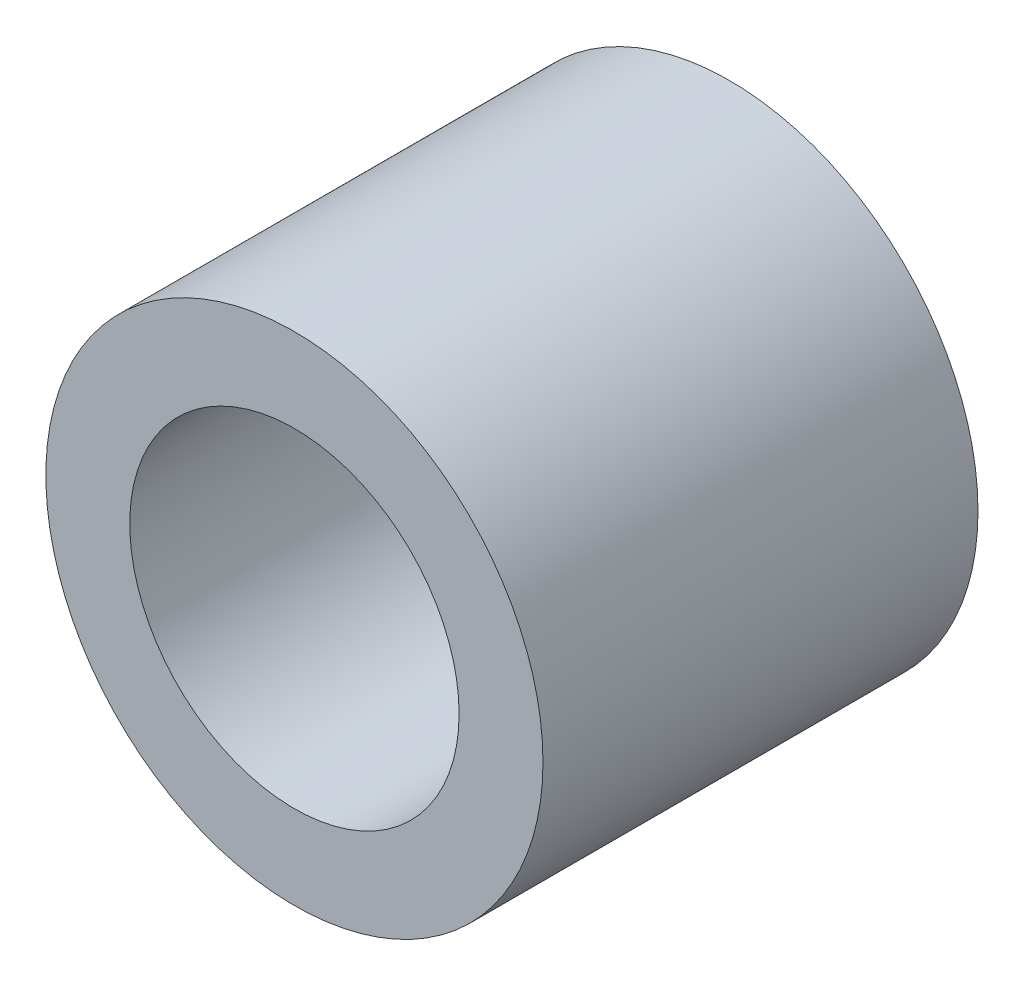
SolidWorks part; units mm, degrees
ref_plane "Front Plane" through (0, 0, 0) normal (0, 0, 1) x (1, 0, 0)
ref_plane "Top Plane" through (0, 0, 0) normal (0, 1, 0) x (1, 0, 0)
ref_plane "Right Plane" through (0, 0, 0) normal (1, 0, 0) x (0, 0, -1)
sketch "Sketch1" plane through (0, 0, 0) normal (0, 0, 1) x (1, 0, 0)
  circle A0 centre (0, 0) radius 4
extrude "Boss-Extrude1" add sketch "Sketch1" along normal blind 7
sketch "Sketch2" plane through (0, 0, 7) normal (0, 0, 1) x (1, 0, 0)
  circle A0 centre (0, 0) radius 2.65
extrude "Cut-Extrude1" cut sketch "Sketch2" against normal up to next
